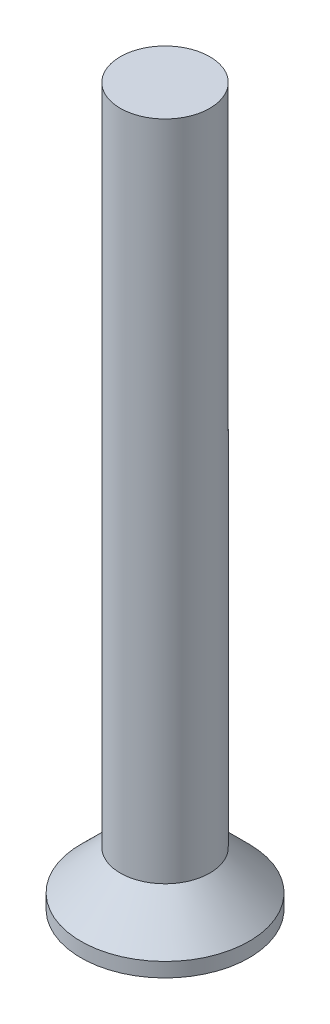
SolidWorks part; units mm, degrees
material "AISI 304"
ref_plane "Front Plane" through (0, 0, 0) normal (0, 0, 1) x (1, 0, 0)
ref_plane "Top Plane" through (0, 0, 0) normal (0, 1, 0) x (1, 0, 0)
ref_plane "Right Plane" through (0, 0, 0) normal (1, 0, 0) x (0, 0, -1)
sketch "Sketch1" plane through (0, 0, 0) normal (0, 1, 0) x (1, 0, 0)
  circle A0 centre (0, 0) radius 1.25
  dimension "D1" = 2.5
extrude "Boss-Extrude1" add sketch "Sketch1" along normal blind 20
sketch "Sketch2" plane through (0, 0, 0) normal (1, 0, 0) x (0, 0, -1)
  line L0 (0, 0) -> (0, 1.5)
  line L1 (0, 1.5) -> (-1.25, 1.5)
  line L2 (-1.25, 20) -> (-1.25, 0) construction
  line L3 (-1.25, 1.5) -> (-2.35, 0.4)
  line L4 (-2.35, 0) -> (0, 0)
  line L5 (-2.35, 0.4) -> (-2.35, 0)
  point P4 (0, 0)
  dimension "D1" = 2.35
  dimension "D2" = 1.5
  dimension "D3" = 45
ref_axis "Axis1" through (0, -0.5, 0) along (0, 1, 0)
revolve "Revolve1" add sketch "Sketch2" angle 360 about axis through (0, -0.5, 0) along (0, 1, 0)
sketch "Sketch3" plane through (0, 0, 0) normal (0, -1, 0) x (1, 0, 0)
  line L0 (-1.5, -0.25) -> (-0.25, -0.25)
  line L1 (1.5, -0.25) -> (-1.5, -0.25) construction
  line L2 (1.5, -0.25) -> (1.5, 0.25) construction
  line L3 (1.5, 0.25) -> (-1.5, 0.25) construction
  line L4 (-1.5, -0.25) -> (-1.5, 0.25) construction
  line L5 (1.5, -0.25) -> (-1.5, 0.25) construction
  line L6 (1.5, 0.25) -> (-1.5, -0.25) construction
  line L7 (-0.25, -1.5) -> (0.25, -1.5) construction
  line L8 (-0.25, -1.5) -> (-0.25, 1.5) construction
  line L9 (-0.25, 1.5) -> (0.25, 1.5) construction
  line L10 (0.25, -1.5) -> (0.25, 1.5) construction
  line L11 (-0.25, -1.5) -> (0.25, 1.5) construction
  line L12 (-0.25, 1.5) -> (0.25, -1.5) construction
  line L13 (-0.25, -0.25) -> (-0.25, -1.5)
  line L14 (-0.25, -1.5) -> (0.25, -1.5)
  line L15 (0.25, -1.5) -> (0.25, -0.25)
  line L16 (0.25, -0.25) -> (1.5, -0.25)
  line L17 (1.5, -0.25) -> (1.5, 0.25)
  line L18 (1.5, 0.25) -> (0.25, 0.25)
  line L19 (0.25, 0.25) -> (0.25, 1.5)
  line L20 (0.25, 1.5) -> (-0.25, 1.5)
  line L21 (-0.25, 1.5) -> (-0.25, 0.25)
  line L22 (-0.25, 0.25) -> (-1.5, 0.25)
  line L23 (-1.5, 0.25) -> (-1.5, -0.25)
  point P0 (0, 0)
  point P6 (0, 0)
  dimension "D1" = 0.5
  dimension "D2" = 3
extrude "Cut-Extrude1" cut sketch "Sketch3" against normal blind 0.5
